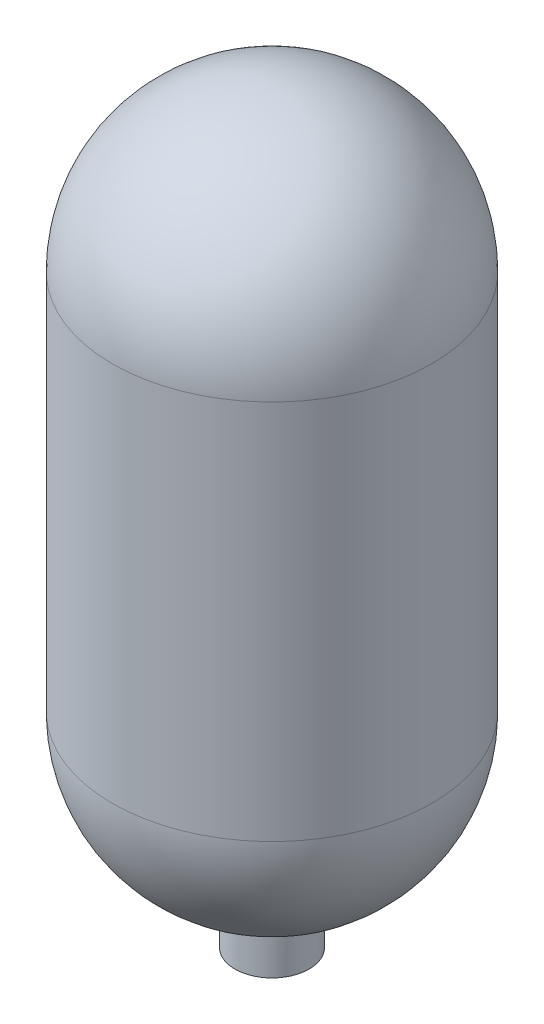
SolidWorks part; units mm, degrees
ref_plane "Front Plane" through (0, 0, 0) normal (0, 0, 1) x (1, 0, 0)
ref_plane "Top Plane" through (0, 0, 0) normal (0, 1, 0) x (1, 0, 0)
ref_plane "Right Plane" through (0, 0, 0) normal (1, 0, 0) x (0, 0, -1)
sketch "Sketch1" plane through (0, 0, 0) normal (0, 0, 1) x (1, 0, 0)
  line L0 (0, 0) -> (0, 747.3154) construction
  line L1 (0, 0) -> (15, 0)
  line L2 (15, 0) -> (15, 20)
  line L3 (64.5, 236.5) -> (64.5, 82.7316)
  line L4 (0, 301) -> (0, 0)
  arc A0 (64.5, 236.5) -> (0, 301) centre (0, 236.5) ccw
  arc A2 (15, 20) -> (64.5, 82.7316) centre (0, 82.7316) ccw
  dimension "D1" = 129
  dimension "D2" = 30
  dimension "D3" = 20
  dimension "D4" = 301
revolve "Revolve1" add sketch "Sketch1" angle 360 about L0
hole_wizard "M18x1.5 Tapped Hole1" positions "Sketch2" profile "Sketch3" tap size "M18x1.5" standard "ANSI Metric"
sketch "Sketch2" plane through (0, 0, 0) normal (0, -1, 0) x (-1, 0, 0)
  point P0 (0, 0)
sketch "Sketch3" plane through (0, 0, 0) normal (1, 0, 0) x (0, 0, -1)
  line L0 (0, 0) -> (0, 20)
  line L1 (0, 20) -> (8.25, 15.0429)
  line L2 (8.25, 15.0429) -> (8.25, 0)
  line L5 (8.25, 0) -> (0, 0)
  line L10 (0, 20) -> (-8.25, 15.0429) construction
  line L11 (0, -6.35) -> (0, 107.95) construction
  dimension "Tap Drill Dia." = 16.5
  dimension "Tap Drill Depth" = 20
  dimension "Drill Angle" = 118
cosmetic thread "Hole Thread1" parameters "D1"=36, "D2"=18
fillet "Fillet1" radius 5 1 edges at (0, 20, -15)
sketch "Sketch4" plane through (0, 0, 0) normal (0, 0, 1) x (1, 0, 0)
  line L0 (0, 0) -> (0, 652.9616) construction
  line L3 (8.25, 15.0429) -> (8.25, 25.7484)
  line L4 (59.5, 82.7316) -> (59.5, 236.5)
  line L5 (59.5, 82.7316) -> (59.5, 236.5)
  line L6 (8.25, 25.7484) -> (17.1223, 25.7484)
  line L7 (8.25, 15.0429) -> (0, 15.0429)
  line L8 (8.25, 15.0429) -> (-8.25, 15.0429) construction
  line L9 (0, 15.0429) -> (0, 296)
  arc A6 (59.5, 236.5) -> (-59.5, 236.5) centre (0, 236.5) ccw
  arc A7 (17.1223, 25.7484) -> (59.5, 82.7316) centre (0, 82.7316) ccw
  arc A8 (59.5, 236.5) -> (0, 296) centre (0, 236.5) ccw
  arc A9 (17.1223, 25.7484) -> (59.5, 82.7316) centre (0, 82.7316) ccw
  dimension "D1" = 5
revolve "Cut-Revolve1" cut sketch "Sketch4" angle 360 about L0
